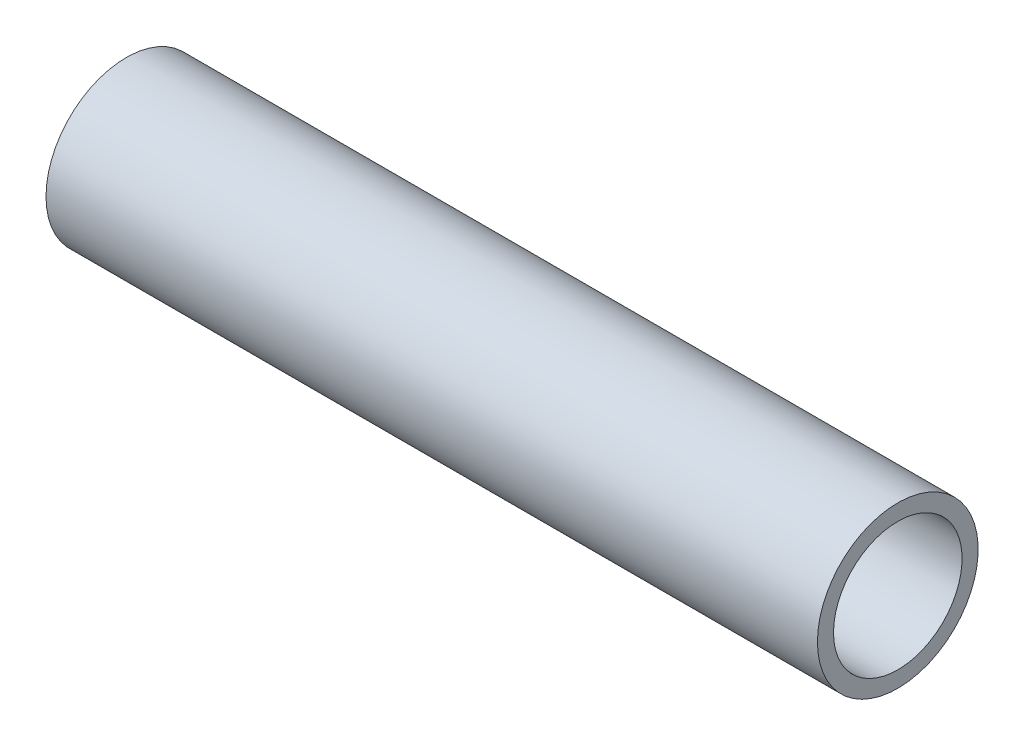
SolidWorks part; units mm, degrees
material "Zoltek Panex 33"
ref_plane "Front Plane" through (0, 0, 0) normal (0, 0, 1) x (1, 0, 0)
ref_plane "Top Plane" through (0, 0, 0) normal (0, 1, 0) x (1, 0, 0)
ref_plane "Right Plane" through (0, 0, 0) normal (1, 0, 0) x (0, 0, -1)
sketch "Sketch1" plane through (0, 0, 0) normal (1, 0, 0) x (0, 0, -1)
  circle A0 centre (0, 0) radius 7.9375
  circle A1 centre (0, 0) radius 6.35
  dimension "D1" = 15.875
  dimension "D2" = 12.7
extrude "Boss-Extrude1" add sketch "Sketch1" along normal mid plane 76.2
